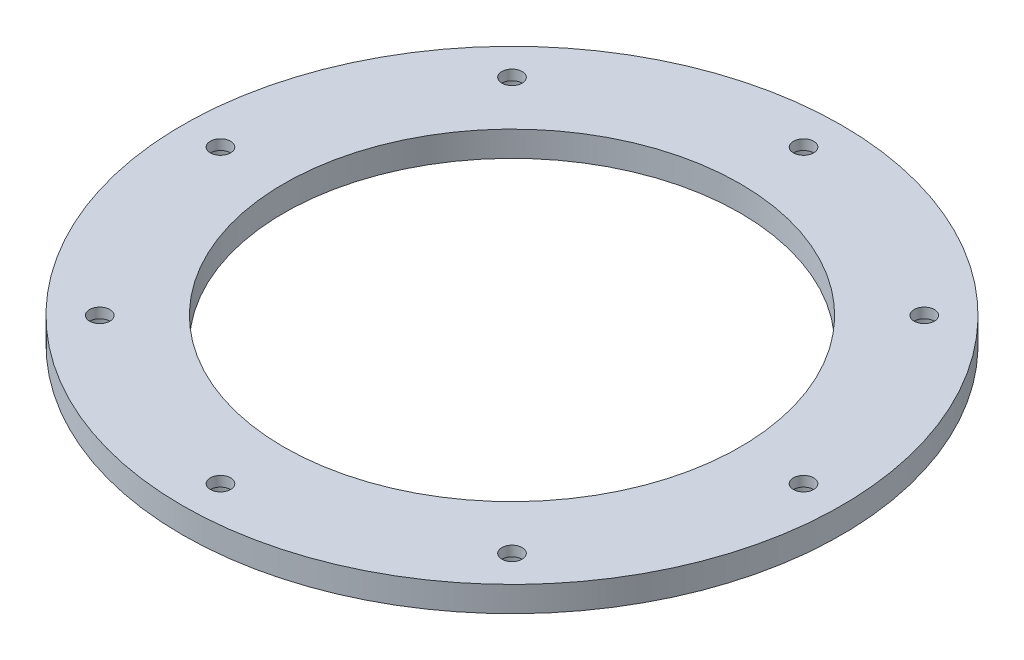
SolidWorks part; units mm, degrees
ref_plane "Front Plane" through (0, 0, 0) normal (0, 0, 1) x (1, 0, 0)
ref_plane "Top Plane" through (0, 0, 0) normal (0, 1, 0) x (1, 0, 0)
ref_plane "Right Plane" through (0, 0, 0) normal (1, 0, 0) x (0, 0, -1)
sketch "Sketch1" plane through (0, 0, 0) normal (0, 1, 0) x (1, 0, 0)
  circle A0 centre (0, 0) radius 130
  circle A1 centre (0, 0) radius 90
  dimension "D1" = 260
  dimension "D2" = 180
extrude "Boss-Extrude1" add sketch "Sketch1" along normal blind 10
sketch "Sketch2" plane through (0, 0, 0) normal (0, -1, 0) x (1, 0, 0)
  line L0 (0, 140.0933) -> (0, -139.7629) construction
  circle A0 centre (0, 115) radius 7.5
  dimension "D2" = 15
  dimension "D1" = 115
extrude "Cut-Extrude1" cut sketch "Sketch2" against normal blind 6
sketch "Sketch3" plane through (0, 6, 0) normal (0, -1, 0) x (1, 0, 0)
  circle A0 centre (0, 115) radius 4
  circle A1 centre (0, 115) radius 7.5
  circle A2 centre (0, 115) radius 7.5 construction
  dimension "D2" = 8
  dimension "D1" = 0
extrude "Cut-Extrude2" cut sketch "Sketch3" against normal up to next and the other way through all
pattern_circular "CirPattern1" count 8 over 360 about axis through (0, 0, 0) along (0, 1, 0) of "Cut-Extrude1", "Cut-Extrude2"
